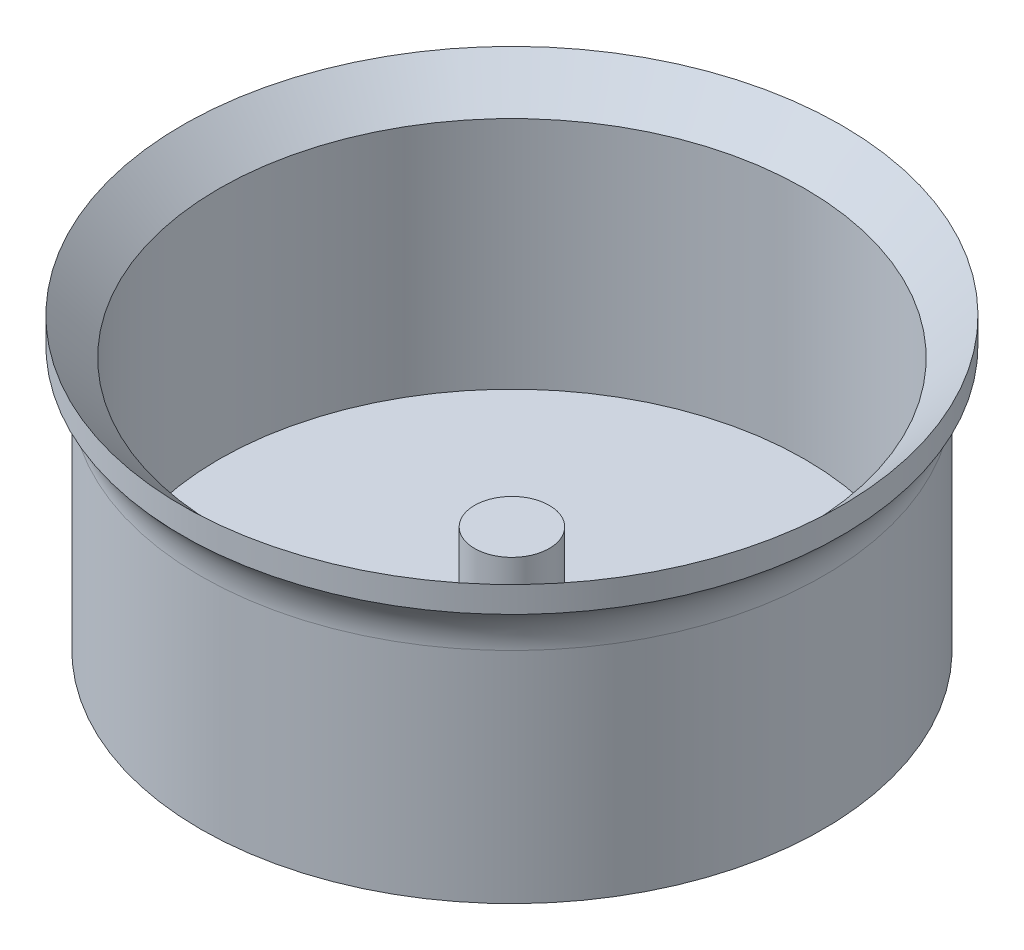
SolidWorks part; units mm, degrees
ref_plane "Front Plane" through (0, 0, 0) normal (0, 0, 1) x (1, 0, 0)
ref_plane "Top Plane" through (0, 0, 0) normal (0, 1, 0) x (1, 0, 0)
ref_plane "Right Plane" through (0, 0, 0) normal (1, 0, 0) x (0, 0, -1)
sketch "Sketch2" plane through (0, 0, 0) normal (1, 0, 0) x (0, 0, -1)
  line L0 (0, 0) -> (0, -6.0614) construction
  line L1 (0, 0) -> (0, 9.2075)
  line L2 (0, 9.2075) -> (3.2385, 9.2075)
  line L3 (3.2385, 9.2075) -> (3.2385, 1.5875)
  line L4 (3.2385, 1.5875) -> (25.4, 1.5875)
  line L5 (25.4, 1.5875) -> (25.4, 21.9075)
  line L6 (25.4, 21.9075) -> (28.575, 25.0825)
  line L7 (28.575, 25.0825) -> (28.575, 22.8374)
  line L9 (26.9875, 19.0049) -> (26.9875, 0)
  line L10 (26.9875, 0) -> (0, 0)
  line L11 (28.575, 22.8374) -> (24.5305, 18.793) construction
  arc A0 (28.575, 22.8374) -> (26.9875, 19.0049) centre (32.4076, 19.0049) ccw
  point P11 (26.9875, 18.8122)
  point P13 (28.575, 22.6212)
  dimension "D1" = 1.5875
  dimension "D2" = 1.5875
  dimension "D3" = 50.8
  dimension "D4" = 6.477
  dimension "D5" = 7.62
  dimension "D6" = 20.32
  dimension "D7" = 1.5875
  dimension "D8" = 3.175
  dimension "D9" = 45
revolve "Revolve1" add sketch "Sketch2" angle 360 about L1
